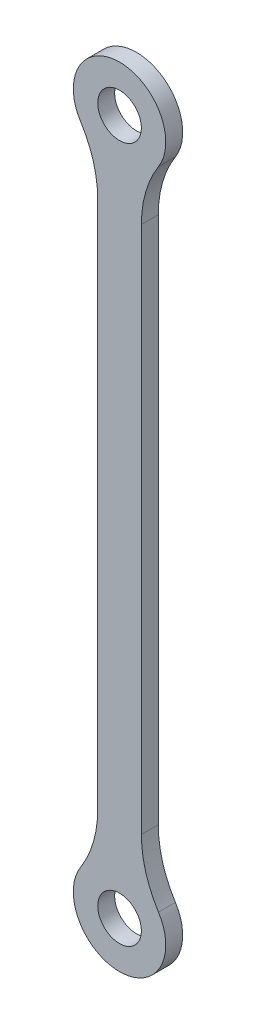
SolidWorks part; units mm, degrees
ref_plane "Front Plane" through (0, 0, 0) normal (0, 0, 1) x (1, 0, 0)
ref_plane "Top Plane" through (0, 0, 0) normal (0, 1, 0) x (1, 0, 0)
ref_plane "Right Plane" through (0, 0, 0) normal (1, 0, 0) x (0, 0, -1)
sketch "Sketch1" plane through (0, 0, 0) normal (0, 0, 1) x (1, 0, 0)
  line L4 (-8, 96.852) -> (-8, -96.852)
  line L5 (8, 96.852) -> (8, -96.852)
  line L6 (0, 127.5) -> (0, -127.5) construction
  line L7 (-8, 0) -> (8, 0) construction
  circle A0 centre (0, 127.5) radius 8
  circle A1 centre (0, -127.5) radius 2.5
  circle A2 centre (0, 127.5) radius 2.5
  circle A3 centre (0, -127.5) radius 8
  arc A6 (-14.2862, -118.3782) -> (14.2862, -118.3782) centre (0, -127.5) ccw
  arc A9 (-8, 96.852) -> (-14.2862, 118.3782) centre (-48, 96.852) ccw
  arc A10 (14.2862, 118.3782) -> (-14.2862, 118.3782) centre (0, 127.5) ccw
  arc A11 (14.2862, 118.3782) -> (8, 96.852) centre (48, 96.852) ccw
  arc A12 (-8, -96.852) -> (-14.2862, -118.3782) centre (-48, -96.852) cw
  arc A13 (14.2862, -118.3782) -> (8, -96.852) centre (48, -96.852) cw
  dimension "D1" = 16
  dimension "D2" = 5
  dimension "D4" = 16.95
  dimension "D5" = 16
  dimension "D7" = 40
  dimension "D3" = 255
  dimension "D6" = 8
extrude "Boss-Extrude1" add sketch "Sketch1" along normal blind 6.2
